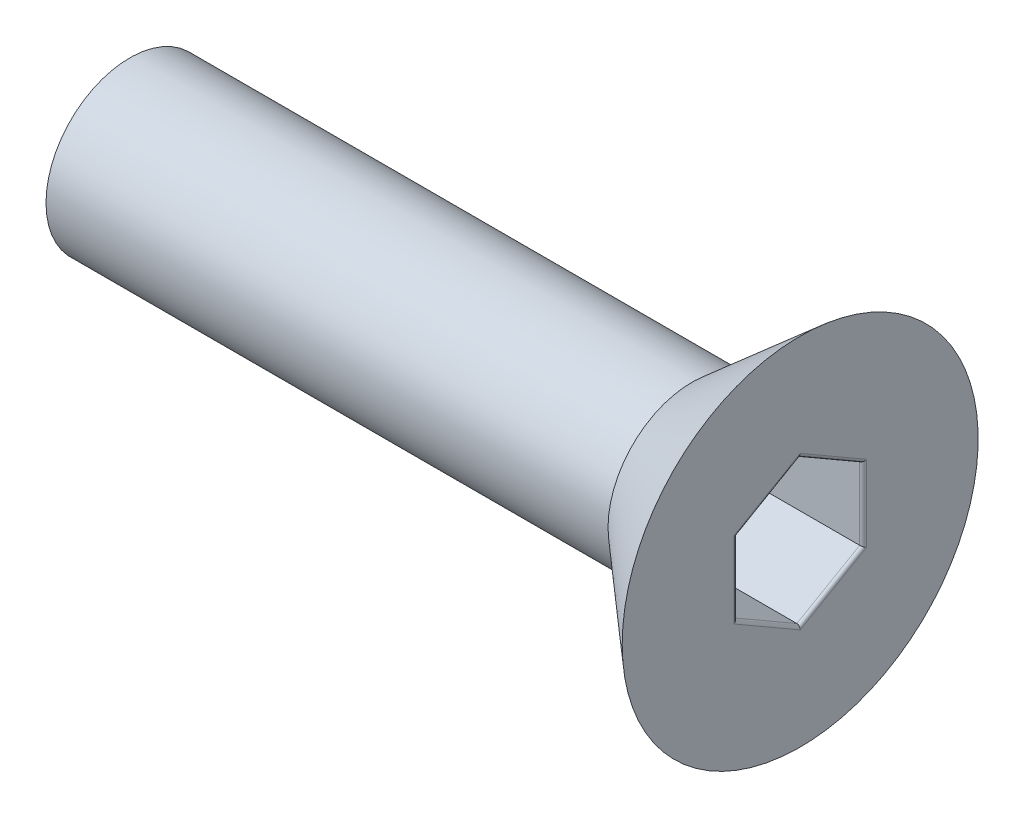
SolidWorks part; units mm, degrees
material "Alloy Steel"
ref_plane "Front Plane" through (0, 0, 0) normal (0, 0, 1) x (1, 0, 0)
ref_plane "Top Plane" through (0, 0, 0) normal (0, 1, 0) x (1, 0, 0)
ref_plane "Right Plane" through (0, 0, 0) normal (1, 0, 0) x (0, 0, -1)
sketch "Sketch1" plane through (0, 0, 0) normal (0, 1, 0) x (1, 0, 0)
  line L0 (0, 0) -> (0, 6.7437)
  line L1 (0, 6.7437) -> (-4.1053, 3.175)
  line L2 (-4.1053, 3.175) -> (-25.4, 3.175)
  line L3 (-25.4, 3.175) -> (-25.4, 0)
  line L4 (-25.4, 0) -> (0, 0)
  dimension "D1" = 3.175
  dimension "D2" = 6.7437
  dimension "D3" = 41
  dimension "D4" = 25.4
revolve "Revolve1" add sketch "Sketch1" angle 360 about L4
sketch "Sketch2" plane through (0, 0, 0) normal (1, 0, 0) x (0, 0, -1)
  line L1 (0, 2.7496) -> (-2.3813, 1.3748)
  line L2 (-2.3813, 1.3748) -> (-2.3813, -1.3748)
  line L3 (-2.3813, -1.3748) -> (0, -2.7496)
  line L4 (0, -2.7496) -> (2.3812, -1.3748)
  line L5 (2.3812, -1.3748) -> (2.3812, 1.3748)
  line L6 (2.3812, 1.3748) -> (0, 2.7496)
  circle A0 centre (0, 0) radius 2.3813 construction
  dimension "D1" = 4.7625
extrude "Cut-Extrude1" cut sketch "Sketch2" against normal blind 3.81
fillet "Fillet1" radius 0.127 6 edges at (0, 0, -2.3812) (0, -2.0622, -1.1906) (0, -2.0622, 1.1906) (0, 0, 2.3813) (0, 2.0622, 1.1906) (0, 2.0622, -1.1906)
